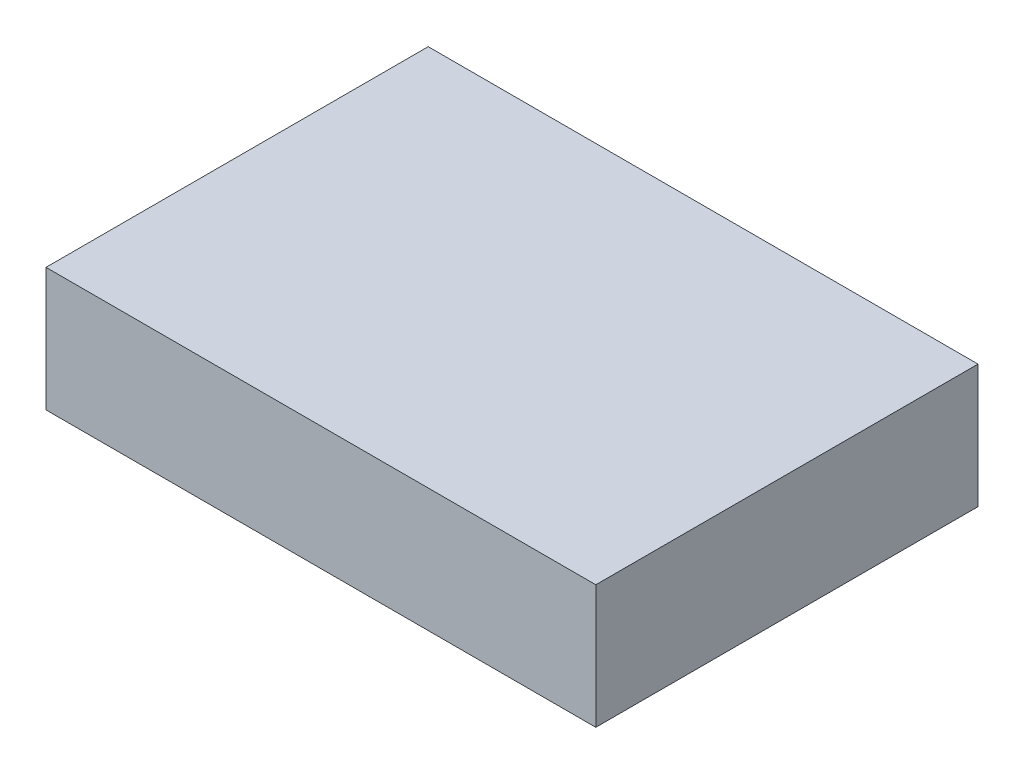
SolidWorks part; units mm, degrees
ref_plane "Front Plane" through (0, 0, 0) normal (0, 0, 1) x (1, 0, 0)
ref_plane "Top Plane" through (0, 0, 0) normal (0, 1, 0) x (1, 0, 0)
ref_plane "Right Plane" through (0, 0, 0) normal (1, 0, 0) x (0, 0, -1)
sketch "Sketch1" plane through (0, 0, 0) normal (0, 1, 0) x (1, 0, 0)
  line L1 (467.5, 0) -> (-467.5, 0)
  line L2 (467.5, 0) -> (467.5, 650)
  line L3 (467.5, 650) -> (-467.5, 650)
  line L4 (-467.5, 0) -> (-467.5, 650)
  dimension "D1" = 935
  dimension "D2" = 650
extrude "Boss-Extrude1" add sketch "Sketch1" against normal blind 210
